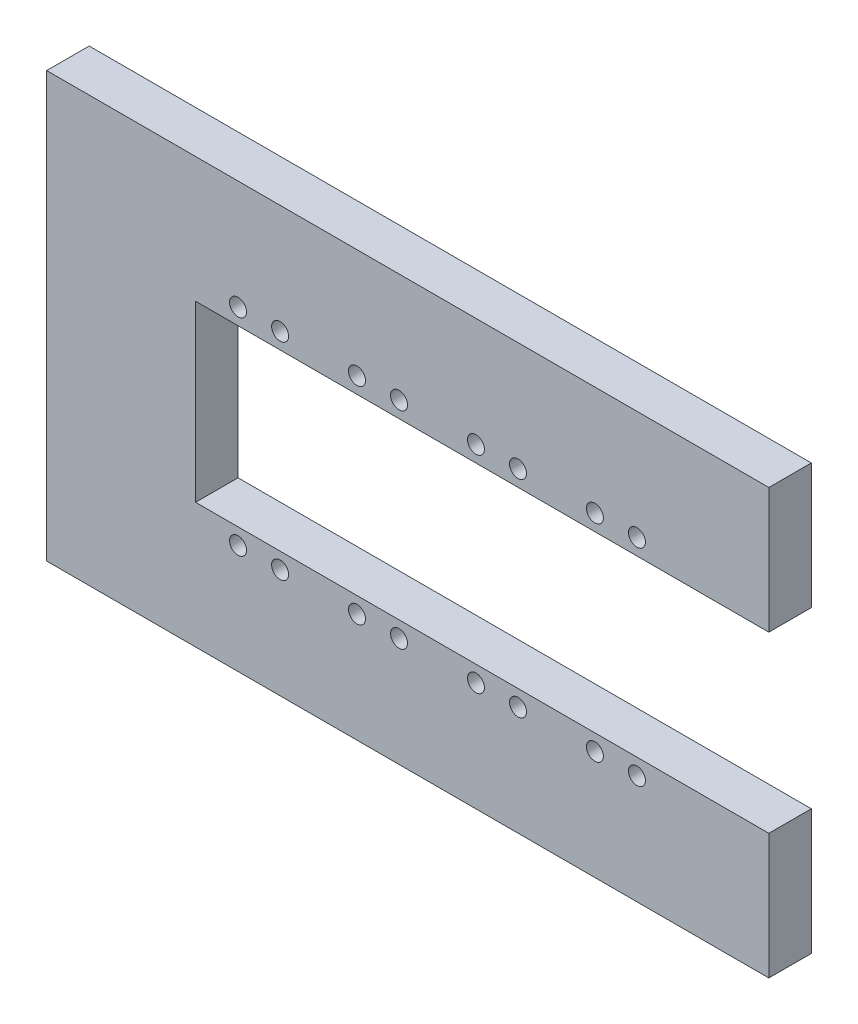
SolidWorks part; units mm, degrees
ref_plane "Front Plane" through (0, 0, 0) normal (0, 0, 1) x (1, 0, 0)
ref_plane "Top Plane" through (0, 0, 0) normal (0, 1, 0) x (1, 0, 0)
ref_plane "Right Plane" through (0, 0, 0) normal (1, 0, 0) x (0, 0, -1)
sketch "Sketch7" plane through (0, 0, 0) normal (0, 0, 1) x (1, 0, 0)
  line L0 (37.1626, 0) -> (172.6077, 0) construction
  line L1 (-50, 50) -> (120, 50)
  line L2 (-50, 50) -> (-50, -50)
  line L3 (-50, -50) -> (120, -50)
  line L4 (120, 50) -> (120, -50)
  point P7 (120, 0)
  dimension "D1" = 50
  dimension "D2" = 100
  dimension "D3" = 170
sketch "Sketch5" [suppressed] plane through (0, 0, 10) normal (0, 0, 1) x (1, 0, 0)
  line L0 (-20, 35) -> (-20, -35) construction
  line L1 (-20, 21.5) -> (11, 21.5)
  line L2 (-20, 21.5) -> (-20, -21.5)
  line L3 (-20, -21.5) -> (11, -21.5)
  line L4 (11, 21.5) -> (11, -21.5)
  line L5 (0, 0) -> (61.9749, 0) construction
  dimension "D1" = 43
  dimension "D2" = 11
extrude "Cut-Extrude1" [suppressed] cut sketch "Sketch5" against normal through all and the other way through all
extrude "Boss-Extrude1" add sketch "Sketch7" against normal blind 10
sketch "Sketch4" plane through (0, 0, 0) normal (0, 0, 1) x (1, 0, 0)
  line L1 (-9.95, -27) -> (9.95, -27) construction
  line L2 (-9.95, -27) -> (-9.95, 27) construction
  line L3 (-9.95, 27) -> (9.95, 27) construction
  line L4 (9.95, -27) -> (9.95, 27) construction
  line L5 (-9.95, -27) -> (9.95, 27) construction
  line L6 (-9.95, 27) -> (9.95, -27) construction
  line L7 (-20, -35) -> (20, -35) construction
  line L8 (-20, -35) -> (-20, 35) construction
  line L9 (-20, 35) -> (20, 35) construction
  line L10 (20, -35) -> (20, 35) construction
  line L11 (-20, -35) -> (20, 35) construction
  line L12 (-20, 35) -> (20, -35) construction
  point P0 (0, 0)
  point P6 (0, 0)
  dimension "D1" = 54
  dimension "D2" = 19.9
  dimension "D3" = 40
  dimension "D4" = 70
sketch "Sketch1" plane through (0, 0, 0) normal (0, 0, 1) x (1, 0, 0)
  line L0 (0, 0) -> (0, 19.8954) construction
  line L1 (0, 0) -> (16.2753, 0) construction
  line L3 (-20, -35) -> (20, -35) construction
  line L4 (-20, -35) -> (-20, 35) construction
  line L5 (-20, 35) -> (20, 35) construction
  line L6 (20, -35) -> (20, 35) construction
  line L7 (-20, -35) -> (20, 35) construction
  line L8 (-20, 35) -> (20, -35) construction
  circle A0 centre (4.95, -24.3) radius 2
  circle A1 centre (-4.95, -24.3) radius 2
  circle A2 centre (-4.95, 24.3) radius 2
  circle A3 centre (4.95, 24.3) radius 2
  dimension "D3" = 9.9
  dimension "D4" = 48.6
  dimension "D5" = 4
  dimension "D1" = 70
  dimension "D2" = 40
extrude "Cut-Extrude2" cut sketch "Sketch1" against normal through all
pattern_linear "LPattern1" count 4 spacing 28 along (1, 0, 0) of "Cut-Extrude2"
sketch "Sketch8" plane through (0, 0, 0) normal (0, 0, 1) x (1, 0, 0)
  line L0 (120, -50) -> (120, 50) construction
  line L1 (-14.95, 20.5) -> (120, 20.5)
  line L2 (-14.95, 20.5) -> (-14.95, -20.5)
  line L3 (-14.95, -20.5) -> (120, -20.5)
  line L4 (120, 20.5) -> (120, -20.5)
  line L6 (-55.093, 0) -> (-17.7872, 0) construction
  line L7 (-9.95, -27) -> (-9.95, 27) construction
  point P11 (-14.95, 0)
  dimension "D1" = 41
  dimension "D2" = 5
extrude "Cut-Extrude3" cut sketch "Sketch8" against normal through all
